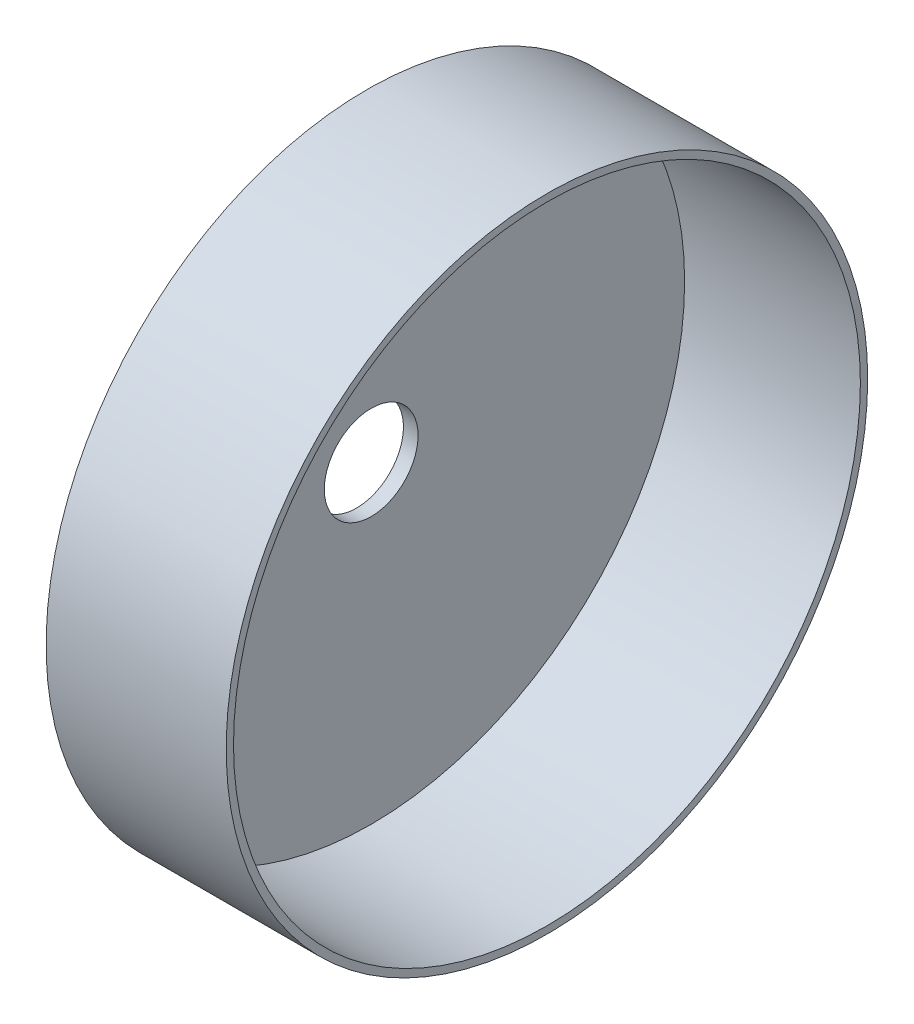
SolidWorks part; units mm, degrees
ref_plane "Front Plane" through (0, 0, 0) normal (1, 0, 0) x (0, 1, 0)
ref_plane "Top Plane" through (0, 0, 0) normal (0, 0, 1) x (0, 1, 0)
ref_plane "Right Plane" through (0, 0, 0) normal (0, 1, 0) x (-1, 0, 0)
sketch "Sketch1" plane through (0, 0, 0) normal (1, 0, 0) x (0, 1, 0)
  circle A0 centre (0, 0) radius 21.9
  dimension "D1" = 43.8
extrude "Boss-Extrude1" add sketch "Sketch1" along normal blind 1
sketch "Sketch2" plane through (1, 0, 0) normal (1, 0, 0) x (0, 1, 0)
  circle A0 centre (0, 0) radius 21.4
  circle A2 centre (0, 0) radius 21.9
  dimension "D1" = 42.8
extrude "Boss-Extrude2" add sketch "Sketch2" along normal blind 12
sketch "Sketch3" plane through (0, 0, 0) normal (-1, 0, 0) x (0, -1, 0)
  circle A0 centre (0, 0) radius 3.2
extrude "Cut-Extrude1" cut sketch "Sketch3" against normal blind 12
sketch "Sketch4" plane through (0, 0, 0) normal (-1, 0, 0) x (0, -1, 0)
  circle A0 centre (0, 0) radius 3.9
  circle A2 centre (0, 0) radius 3.2
  dimension "D1" = 7.8
chamfer "Chamfer1" distance 4 angle 10 1 edges at (0, 0, -21.9)
